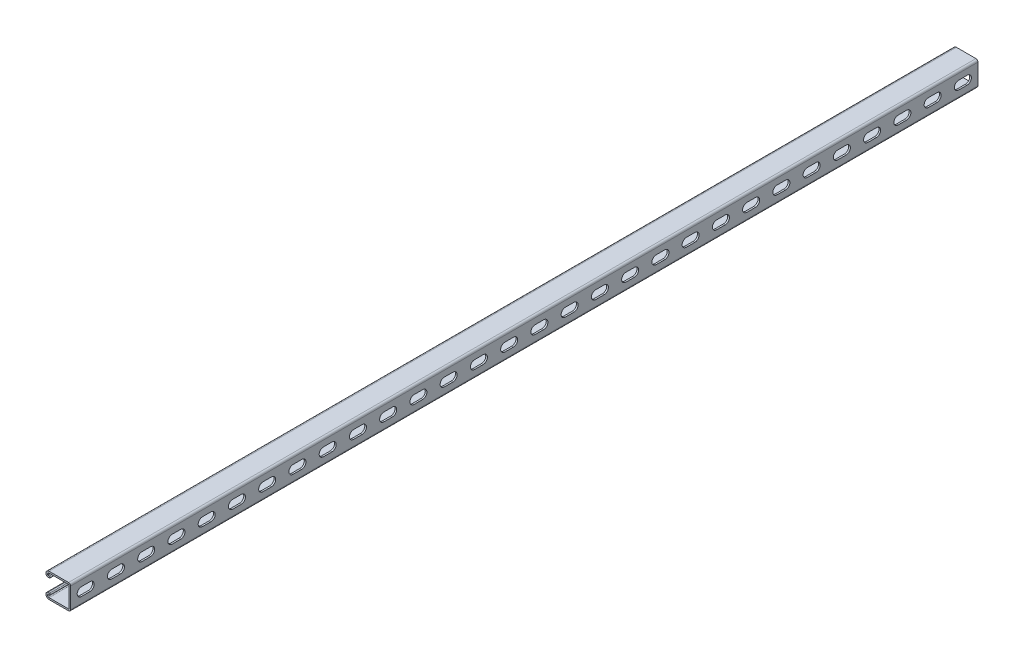
SolidWorks part; units mm, degrees
material "Galvanized Steel"
ref_plane "Front Plane" through (0, 0, 0) normal (0, 0, 1) x (1, 0, 0)
ref_plane "Top Plane" through (0, 0, 0) normal (0, 1, 0) x (1, 0, 0)
ref_plane "Right Plane" through (0, 0, 0) normal (1, 0, 0) x (0, 0, -1)
sketch "Sketch1" plane through (0, 0, 0) normal (0, 0, 1) x (1, 0, 0)
  line L0 (0, 0) -> (-41.275, 0) construction
  line L3 (-41.275, 20.6375) -> (0, 20.6375) construction
  line L4 (-41.275, 20.6375) -> (-41.275, -20.6375) construction
  line L5 (-41.275, -20.6375) -> (0, -20.6375) construction
  line L6 (0, 20.6375) -> (0, -20.6375) construction
  line L7 (-36.2267, 20.6375) -> (-3.4607, 20.6375)
  line L8 (0, 17.1767) -> (0, -17.1767)
  line L9 (-2.794, -17.1767) -> (-2.794, 17.1767)
  line L10 (-3.4608, 17.8435) -> (-36.2267, 17.8435)
  line L11 (-41.275, 15.5892) -> (-41.275, 14.5732)
  line L12 (-37.8142, 11.1125) -> (-35.5346, 11.1125)
  line L14 (-35.5346, 13.9065) -> (-37.8142, 13.9065)
  line L15 (-38.481, 14.5732) -> (-38.481, 15.5892)
  line L16 (-38.481, -14.5733) -> (-38.481, -15.5893)
  line L17 (-35.5346, -13.9065) -> (-37.8142, -13.9065)
  line L18 (-37.8142, -11.1125) -> (-35.5346, -11.1125)
  line L19 (-41.275, -15.5893) -> (-41.275, -14.5733)
  line L20 (-3.4607, -17.8435) -> (-36.2267, -17.8435)
  line L21 (-36.2267, -20.6375) -> (-3.4607, -20.6375)
  line L22 (-2.794, -20.6375) -> (-2.794, 20.6375) construction
  arc A1 (0, 17.1767) -> (-3.4607, 20.6375) centre (-3.4607, 17.1767) ccw
  arc A2 (-2.794, 17.1767) -> (-3.4608, 17.8435) centre (-3.4607, 17.1767) ccw
  arc A4 (-36.2267, 20.6375) -> (-41.275, 15.5892) centre (-36.2267, 15.5892) ccw
  arc A5 (-41.275, 14.5732) -> (-37.8142, 11.1125) centre (-37.8142, 14.5732) ccw
  arc A6 (-35.5346, 11.1125) -> (-35.5346, 13.9065) centre (-35.5346, 12.5095) ccw
  arc A7 (-37.8142, 13.9065) -> (-38.481, 14.5732) centre (-37.8142, 14.5732) cw
  arc A8 (-38.481, 15.5892) -> (-36.2267, 17.8435) centre (-36.2267, 15.5892) cw
  arc A9 (-38.481, -15.5893) -> (-36.2267, -17.8435) centre (-36.2267, -15.5893) ccw
  arc A10 (-37.8142, -13.9065) -> (-38.481, -14.5733) centre (-37.8142, -14.5733) ccw
  arc A11 (-35.5346, -11.1125) -> (-35.5346, -13.9065) centre (-35.5346, -12.5095) cw
  arc A12 (-41.275, -14.5733) -> (-37.8142, -11.1125) centre (-37.8142, -14.5733) cw
  arc A13 (-36.2267, -20.6375) -> (-41.275, -15.5893) centre (-36.2267, -15.5893) cw
  arc A14 (-2.794, -17.1767) -> (-3.4607, -17.8435) centre (-3.4607, -17.1767) cw
  arc A15 (0, -17.1767) -> (-3.4607, -20.6375) centre (-3.4607, -17.1767) cw
  point P24 (0, 20.6375)
  point P65 (-2.794, 0)
  dimension "D1" = 3.4608
  dimension "D2" = 5.0482
  dimension "D3" = 3.4608
  dimension "Ht." = 41.275
  dimension "Wd." = 41.275
  dimension "Thk." = 2.794
  dimension "D4" = 9.525
  dimension "D5" = 7.1374
extrude "Boss-Extrude1" add sketch "Sketch1" against normal blind 1524
sketch "Sketch3" plane through (0, 0, 0) normal (1, 0, 0) x (0, 0, -1)
  line L0 (0, 0) -> (1524, 0) construction
  point P2 (101.6, 0)
  point P3 (1422.4, 0)
  dimension "D1" = 101.6
  dimension "D2" = 101.6
  dimension "D3" = 1524
sketch "Sketch2" plane through (0, 0, 0) normal (1, 0, 0) x (0, 0, -1)
  line L0 (18.2562, 0) -> (32.5437, 0) construction
  line L1 (18.2562, 7.1437) -> (32.5437, 7.1437)
  line L2 (18.2562, -7.1437) -> (32.5437, -7.1437)
  line L3 (18.2562, 0) -> (0, 0) construction
  line L4 (25.4, 0) -> (76.2, 0) construction
  line L5 (0, -17.1767) -> (0, 17.1767) construction
  arc A0 (18.2562, 7.1437) -> (18.2562, -7.1437) centre (18.2562, 0) ccw
  arc A1 (32.5437, -7.1437) -> (32.5437, 7.1437) centre (32.5437, 0) ccw
  point P3 (25.4, 0)
  dimension "Hole to End" = 11.1125
  dimension "D2" = 25.4
extrude "Cut-Extrude1" cut sketch "Sketch2" against normal up to vertex (2.794 mm away) up to point (-2.794, 0, 0)
pattern_linear "LPattern1" count 30 spacing 50.8 along (0, 0, -1) of "Cut-Extrude1"
equation "\"D1@LPattern1\" = \"Slot Ctr.@Sketch2\""
equation "\"Hole Count@LPattern1\" = \"Lg.@Boss-Extrude1\" / \"D1@LPattern1\""
equation "\"D3@Sketch3\" = \"Lg.@Boss-Extrude1\""
